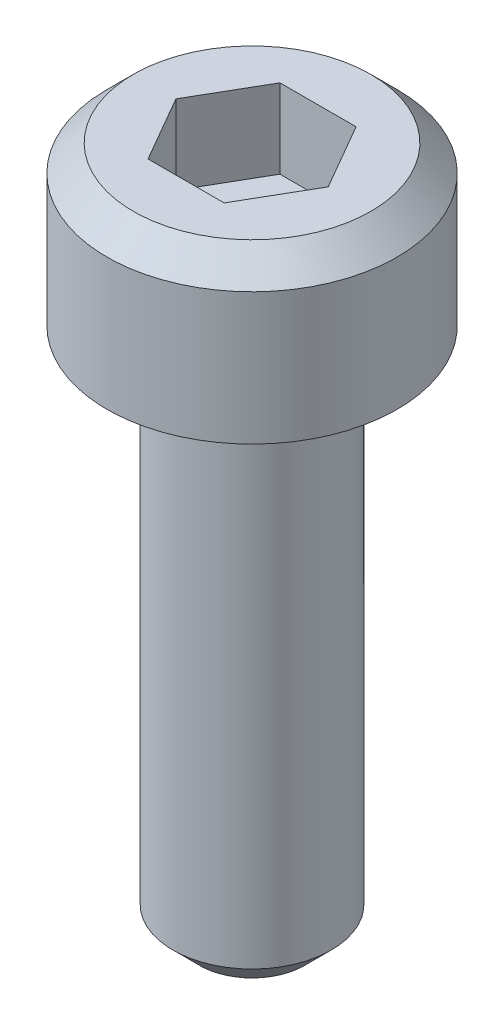
SolidWorks part; units mm, degrees
ref_plane "Front Plane" through (0, 0, 0) normal (0, 0, 1) x (1, 0, 0)
ref_plane "Top Plane" through (0, 0, 0) normal (0, 1, 0) x (1, 0, 0)
ref_plane "Right Plane" through (0, 0, 0) normal (1, 0, 0) x (0, 0, -1)
sketch "Sketch1" plane through (0, 0, 0) normal (0, 0, 1) x (1, 0, 0)
  line L0 (0, 0) -> (0, 15.7991) construction
  line L1 (0, 13) -> (-2.25, 13)
  line L2 (-2.75, 12.5) -> (-2.75, 10)
  line L3 (-2.75, 10) -> (-1.5, 10)
  line L4 (-1.5, 10) -> (-1.5, 0.5)
  line L5 (-1, 0) -> (0, 0)
  line L6 (0, 13) -> (0, 0)
  line L7 (-2.25, 13) -> (-2.75, 12.5)
  line L8 (-1.5, 0.5) -> (-1, 0)
  line L9 (0, 13) -> (-10, 13) construction
  point P4 (-2.75, 13)
  point P8 (-1.5, 0)
  dimension "D1" = 3
  dimension "D2" = 10
  dimension "D3" = 3
  dimension "D4" = 5.5
  dimension "D5" = 10
revolve "Revolve1" add sketch "Sketch1" angle 360 about L0
sketch "Sketch2" plane through (0, 13, 0) normal (0, 1, 0) x (1, 0, 0)
  line L0 (0, 0) -> (-2.9941, 0) construction
  line L1 (-1.4434, 0) -> (-0.7217, -1.25)
  line L2 (-0.7217, -1.25) -> (0.7217, -1.25)
  line L3 (0.7217, -1.25) -> (1.4434, 0)
  line L4 (1.4434, 0) -> (0.7217, 1.25)
  line L5 (0.7217, 1.25) -> (-0.7217, 1.25)
  line L6 (-0.7217, 1.25) -> (-1.4434, 0)
  line L7 (-0.7217, 1.25) -> (-1.9717, 0) construction
  line L8 (0, 0) -> (-10, 0) construction
  circle A0 centre (0, 0) radius 1.25 construction
  dimension "D1" = 2.5
  dimension "D2" = 45
extrude "Cut-Extrude1" cut sketch "Sketch2" against normal blind 1.5
